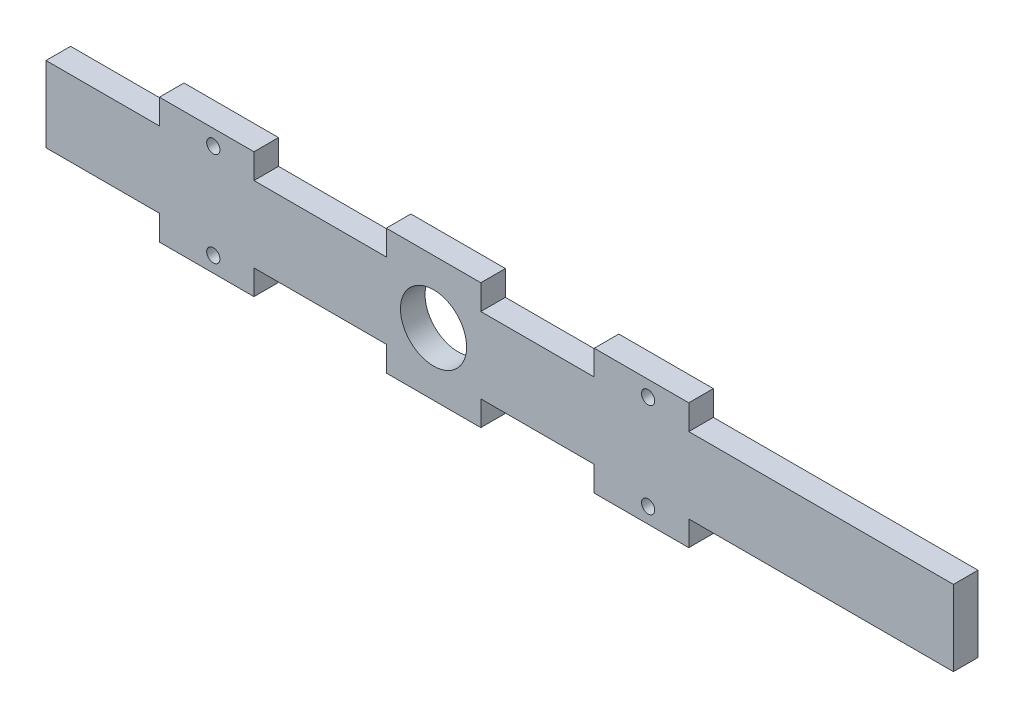
SolidWorks part; units mm, degrees
ref_plane "Alzado" through (0, 0, 0) normal (0, 0, 1) x (1, 0, 0)
ref_plane "Planta" through (0, 0, 0) normal (0, 1, 0) x (1, 0, 0)
ref_plane "Vista lateral" through (0, 0, 0) normal (1, 0, 0) x (0, 0, -1)
sketch "Sketch1" plane through (0, 0, 0) normal (0, 0, 1) x (1, 0, 0)
  line L1 (-103.144, 33.1959) -> (-53.144, 33.1959)
  line L2 (-53.144, 33.1959) -> (-53.144, 20)
  line L4 (126.856, 20) -> (126.856, 33.1959)
  line L5 (126.856, 33.1959) -> (176.856, 33.1959)
  line L6 (176.856, 33.1959) -> (176.856, 20)
  line L7 (176.856, 20) -> (316.856, 20)
  line L19 (316.856, -20) -> (316.856, 20)
  line L20 (-103.144, 20) -> (-163.144, 20)
  line L21 (-163.144, 20) -> (-163.144, -20)
  line L22 (16.856, 20) -> (16.856, 33.1959)
  line L23 (16.856, 33.1959) -> (66.856, 33.1959)
  line L24 (66.856, 33.1959) -> (66.856, 20)
  line L25 (-53.144, 20) -> (16.856, 20)
  line L26 (66.856, 20) -> (126.856, 20)
  line L27 (-103.144, 33.1959) -> (-103.144, 20)
  line L29 (-103.144, -33.1959) -> (-103.144, -20)
  line L30 (66.856, -20) -> (126.856, -20)
  line L31 (-53.144, -20) -> (16.856, -20)
  line L32 (66.856, -33.1959) -> (66.856, -20)
  line L33 (16.856, -33.1959) -> (66.856, -33.1959)
  line L34 (16.856, -20) -> (16.856, -33.1959)
  line L35 (-103.144, -20) -> (-163.144, -20)
  line L36 (176.856, -20) -> (316.856, -20)
  line L37 (176.856, -33.1959) -> (176.856, -20)
  line L38 (126.856, -33.1959) -> (176.856, -33.1959)
  line L39 (126.856, -20) -> (126.856, -33.1959)
  line L40 (-53.144, -33.1959) -> (-53.144, -20)
  line L41 (-103.144, -33.1959) -> (-53.144, -33.1959)
  circle A0 centre (-74.644, 25) radius 3.5
  circle A1 centre (155.356, 25) radius 3.5
  circle A2 centre (155.356, -25) radius 3.5
  circle A3 centre (-74.644, -25) radius 3.5
  dimension "D5" = 7
  dimension "D7" = 7
  dimension "D8" = 480
  dimension "D2" = 50
  dimension "D3" = 180
  dimension "D4" = 50
  dimension "D6" = 60
  dimension "D9" = 25
  dimension "D10" = 50
  dimension "D11" = 25
  dimension "D12" = 70
  dimension "D13" = 40
  dimension "D14" = 230
  dimension "D15" = 40
  dimension "D16" = 20
  dimension "D17" = 20
extrude "Boss-Extrude1" add sketch "Sketch1" along normal blind 13
hole_wizard "Ø25.0mm Dowel Hole1" positions "3DSketch1" profile "Sketch3" hole size "Ø25.0" standard "ISO" end condition through all
sketch3d "3DSketch1"
  line L0 (16.856, 33.1959, 13) -> (16.856, 20, 13) construction
  point P0 (41.856, 0, 13)
  dimension "D1" = 25
sketch "Sketch3" plane through (41.856, 0, 13) normal (1, 0, 0) x (0, -1, 0)
  line L0 (0, 0) -> (0, 13)
  line L1 (0, 13) -> (17.5, 13)
  line L2 (17.5, 13) -> (17.5, 0)
  line L5 (17.5, 0) -> (0, 0)
  line L11 (0, -6.35) -> (0, 107.95) construction
  dimension "Thru Hole Dia." = 35
  dimension "Thru Hole Depth" = 13
